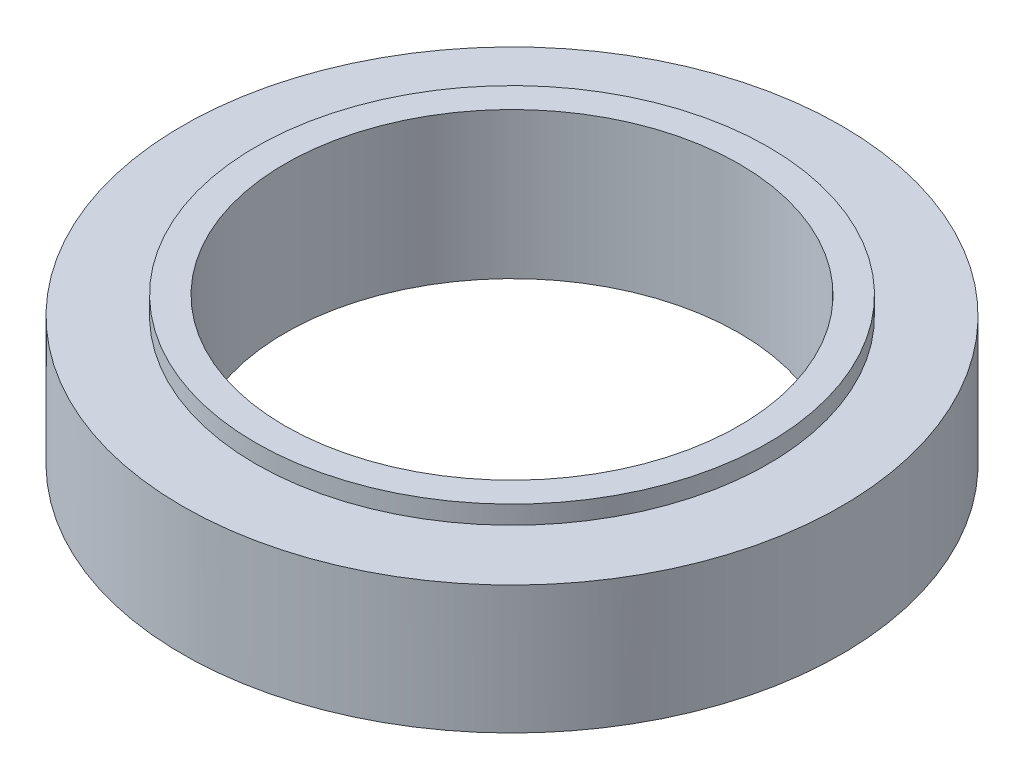
SolidWorks part; units mm, degrees
ref_plane "前视基准面" through (0, 0, 0) normal (0, 0, 1) x (1, 0, 0)
ref_plane "上视基准面" through (0, 0, 0) normal (0, 1, 0) x (1, 0, 0)
ref_plane "右视基准面" through (0, 0, 0) normal (1, 0, 0) x (0, 0, -1)
sketch "草图1" plane through (0, 0, 0) normal (0, 1, 0) x (1, 0, 0)
  circle A0 centre (0, 0) radius 6.2
  circle A1 centre (0, 0) radius 7
  dimension "D1" = 12.4
  dimension "D2" = 14
extrude "凸台-拉伸1" add sketch "草图1" along normal blind 4
sketch "草图2" plane through (0, 0, 0) normal (0, -1, 0) x (1, 0, 0)
  circle A0 centre (0, 0) radius 9
  circle A1 centre (0, 0) radius 7 construction
  circle A2 centre (0, 0) radius 7
  dimension "D1" = 18
extrude "凸台-拉伸2" add sketch "草图2" against normal offset from surface (3.5 mm away) 0.5 up to face at (0, 4, 7)
